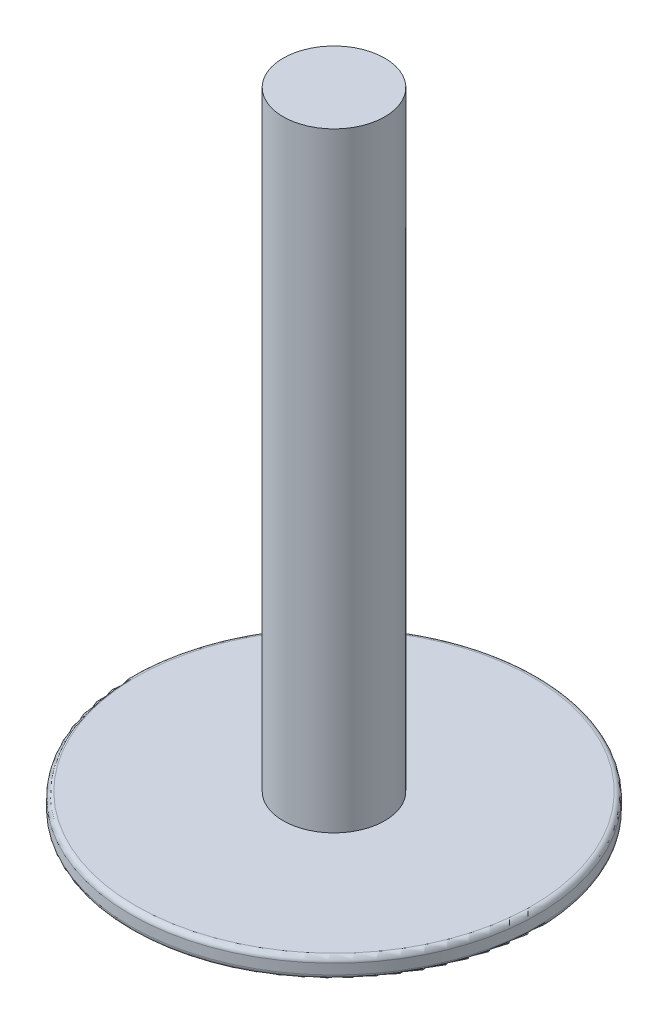
SolidWorks part; units mm, degrees
material "AISI 4140 Steel, quenched & tempered"
ref_plane "Front Plane" through (0, 0, 0) normal (1, 0, 0) x (0, 1, 0)
ref_plane "Top Plane" through (0, 0, 0) normal (0, 0, 1) x (0, 1, 0)
ref_plane "Right Plane" through (0, 0, 0) normal (0, 1, 0) x (-1, 0, 0)
sketch "Sketch1" plane through (0, 0, 0) normal (1, 0, 0) x (0, 1, 0)
  line L0 (-21.912, 0) -> (25.327, 0) construction
  line L1 (0, 30.1451) -> (0, -21.3064) construction
  line L2 (0, 5) -> (60, 5)
  line L3 (60, 5) -> (60, 0)
  line L4 (60, 0) -> (0, 0)
  line L5 (0, 0) -> (0, 5)
  line L7 (0, 20) -> (-2, 20)
  line L8 (-2, 20) -> (-2, 0)
  line L9 (-2, 0) -> (0, 0)
  line L10 (0, 20) -> (0, 5)
  line L11 (-10, 0) -> (-2, 0)
  arc A1 (-2, 15) -> (-10, 0) centre (4.9052, 1.6839) ccw
  dimension "D5" = 8
  dimension "D7" = 15
  dimension "D1" = 10
  dimension "D2" = 60
  dimension "D3" = 2
  dimension "D4" = 40
  dimension "D6" = 30
revolve "Revolve1" add sketch "Sketch1" angle 360 about L0
sketch "Sketch2" plane through (0, -2, 0) normal (0, -1, 0) x (1, 0, 0)
  line L7 (4, -6.9282) -> (8, 0)
  line L8 (8, 0) -> (4, 6.9282)
  line L9 (4, 6.9282) -> (-4, 6.9282)
  line L10 (-4, 6.9282) -> (-8, 0)
  line L11 (-8, 0) -> (-4, -6.9282)
  line L12 (-4, -6.9282) -> (4, -6.9282)
  circle A0 centre (0, 0) radius 8 construction
  dimension "D1" = 8
extrude "Cut-Extrude1" cut sketch "Sketch2" along normal blind 10 from offset 1
fillet "Fillet1" radius 0.5 20 edges at (0, 0, -20) (0, -2, -20) (0, -3, -6.9282) (0, -3, 6.9282) (0.4533, -9.1427, 6.9282) (-0.4533, -9.1427, -6.9282) (6, -3, -3.4641) (6, -3, 3.4641) (-6, -3, 3.4641) (-6, -3, -3.4641) (-4, -5.8501, -6.9282) (-4, -5.8501, 6.9282) (4, -5.8501, 6.9282) (8, -5.8501, 0) (4, -5.8501, -6.9282) (-5.0295, -9.0457, -5.145) (-6.9705, -9.0457, 1.7832) (5.0295, -9.0457, 5.145) (6.9705, -9.0457, -1.7832) (-8, -5.8501, 0)
